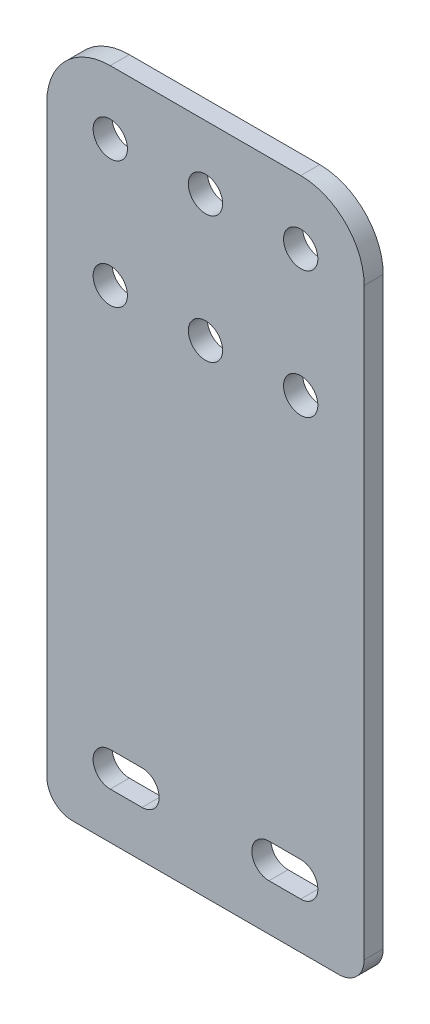
SolidWorks part; units mm, degrees
ref_plane "Ebene vorne" through (0, 0, 0) normal (0, 0, 1) x (1, 0, 0)
ref_plane "Ebene oben" through (0, 0, 0) normal (0, 1, 0) x (1, 0, 0)
ref_plane "Ebene rechts" through (0, 0, 0) normal (1, 0, 0) x (0, 0, -1)
sketch "Model" plane through (0, 0, 0) normal (0, 0, 1) x (1, 0, 0)
  line L0 (40, 106) -> (10, 106)
  line L1 (0, 96) -> (0, 4)
  line L2 (4, 0) -> (46, 0)
  line L3 (50, 4) -> (50, 96)
  line L4 (15, 7.3) -> (10, 7.3)
  line L5 (10, 12.7) -> (15, 12.7)
  line L6 (40, 7.3) -> (35, 7.3)
  line L7 (35, 12.7) -> (40, 12.7)
  circle A0 centre (25, 76) radius 2.7
  circle A1 centre (25, 96) radius 2.7
  circle A2 centre (40, 76) radius 2.7
  circle A3 centre (40, 96) radius 2.7
  circle A4 centre (10, 76) radius 2.7
  circle A5 centre (10, 96) radius 2.7
  arc A6 (10, 106) -> (0, 96) centre (10, 96) ccw
  arc A7 (0, 4) -> (4, 0) centre (4, 4) ccw
  arc A8 (46, 0) -> (50, 4) centre (46, 4) ccw
  arc A9 (50, 96) -> (40, 106) centre (40, 96) ccw
  arc A10 (10, 12.7) -> (10, 7.3) centre (10, 10) ccw
  arc A11 (15, 7.3) -> (15, 12.7) centre (15, 10) ccw
  arc A12 (35, 12.7) -> (35, 7.3) centre (35, 10) ccw
  arc A13 (40, 7.3) -> (40, 12.7) centre (40, 10) ccw
extrude "Aufsatz-Linear austragen1" add sketch "Model" along normal blind 3
